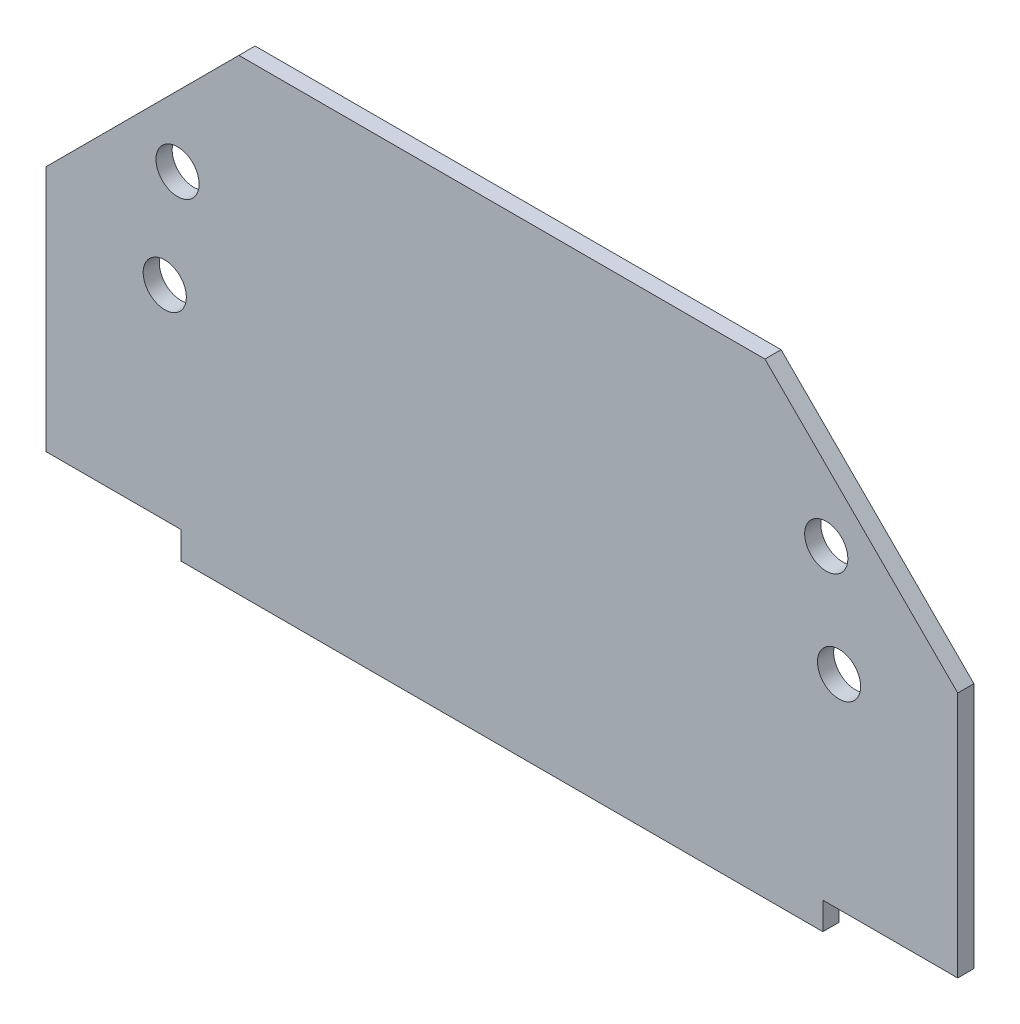
SolidWorks part; units mm, degrees
ref_plane "Front Plane" through (0, 0, 0) normal (0, 0, 1) x (1, 0, 0)
ref_plane "Top Plane" through (0, 0, 0) normal (0, 1, 0) x (1, 0, 0)
ref_plane "Right Plane" through (0, 0, 0) normal (1, 0, 0) x (0, 0, -1)
sketch "Sketch1" plane through (0, 0, 0) normal (0, 0, 1) x (1, 0, 0)
  line L0 (-33.8, 12.7868) -> (-33.8, 31.0897)
  line L1 (0, 46.5868) -> (0, 7.2632) construction
  line L4 (-33.8, 31.0897) -> (-19.5029, 45.3868)
  line L6 (-19.5029, 45.3868) -> (19.5029, 45.3868)
  line L7 (-33.8, 12.7868) -> (-23.8, 12.7868)
  line L9 (-23.8, 12.7868) -> (-23.8, 10.7588)
  line L11 (-23.8, 10.7588) -> (23.8, 10.7588)
  line L12 (23.8, 12.7868) -> (23.8, 10.7588)
  line L13 (33.8, 12.7868) -> (23.8, 12.7868)
  line L14 (33.8, 12.7868) -> (33.8, 31.0897)
  line L15 (33.8, 31.0897) -> (19.5029, 45.3868)
  circle A4 centre (-25, 27.9006) radius 1.6
  circle A7 centre (25, 27.9006) radius 1.6
  circle A8 centre (-24.0525, 35.6393) radius 1.6
  circle A9 centre (24.0525, 35.6393) radius 1.6
  point P21 (0, 10.7588)
  point P25 (0, 45.3868)
extrude "Boss-Extrude1" add sketch "Sketch1" along normal blind 1.2
